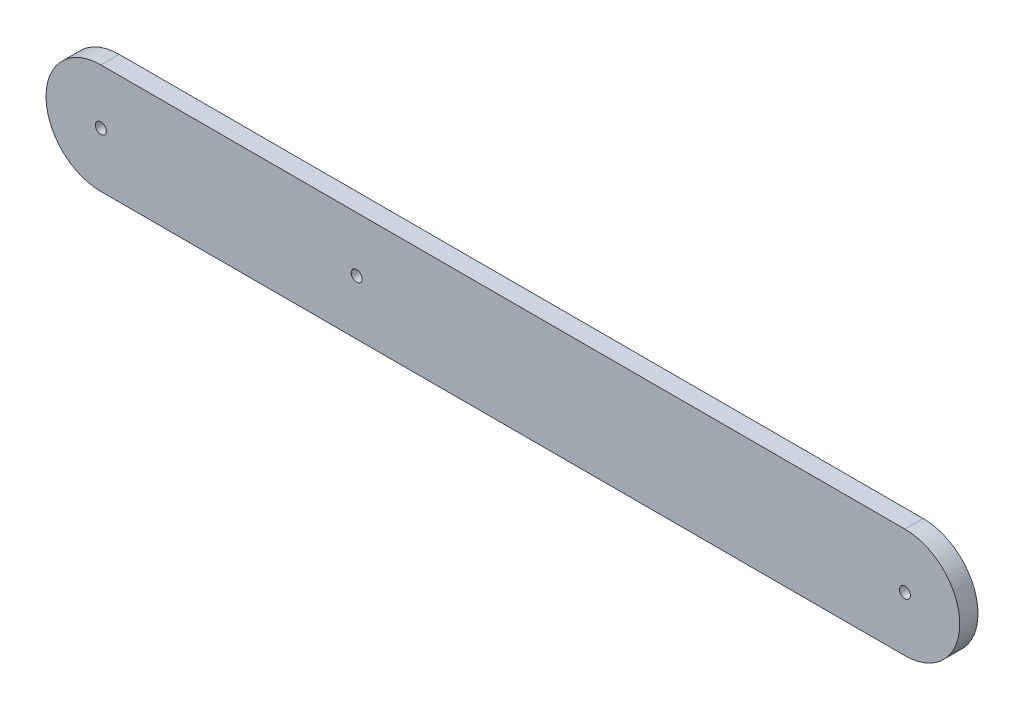
SolidWorks part; units mm, degrees
material "PVC 0.007 Plasticized"
ref_plane "Front Plane" through (0, 0, 0) normal (0, 0, 1) x (1, 0, 0)
ref_plane "Top Plane" through (0, 0, 0) normal (0, 1, 0) x (1, 0, 0)
ref_plane "Right Plane" through (0, 0, 0) normal (1, 0, 0) x (0, 0, -1)
sketch "Sketch1" plane through (0, 0, 0) normal (0, 0, 1) x (1, 0, 0)
  line L0 (0, 0) -> (150, 0)
  dimension "D1" = 150
sketch "Sketch2" plane through (0, 0, 0) normal (0, 0, 1) x (1, 0, 0)
  line L0 (0, 0) -> (-70, 0)
  dimension "D1" = 70
sketch "Sketch3" plane through (0, 0, 0) normal (0, 0, 1) x (1, 0, 0)
  line L0 (-70, 15) -> (150, 15)
  line L1 (-70, -15) -> (150, -15)
  arc A0 (-70, 15) -> (-70, -15) centre (-70, 0) ccw
  arc A1 (150, -15) -> (150, 15) centre (150, 0) ccw
  dimension "D1" = 30
  dimension "D2" = 30
extrude "Boss-Extrude1" add sketch "Sketch3" along normal blind 5
sketch "Sketch4" plane through (0, 0, 0) normal (0, 0, -1) x (-1, 0, 0)
  circle A0 centre (-150, 0) radius 1.5
  circle A1 centre (0, 0) radius 1.5
  circle A2 centre (70, 0) radius 1.5
  dimension "D1" = 3
  dimension "D2" = 3
  dimension "D3" = 3
extrude "Cut-Extrude1" cut sketch "Sketch4" against normal blind 5
